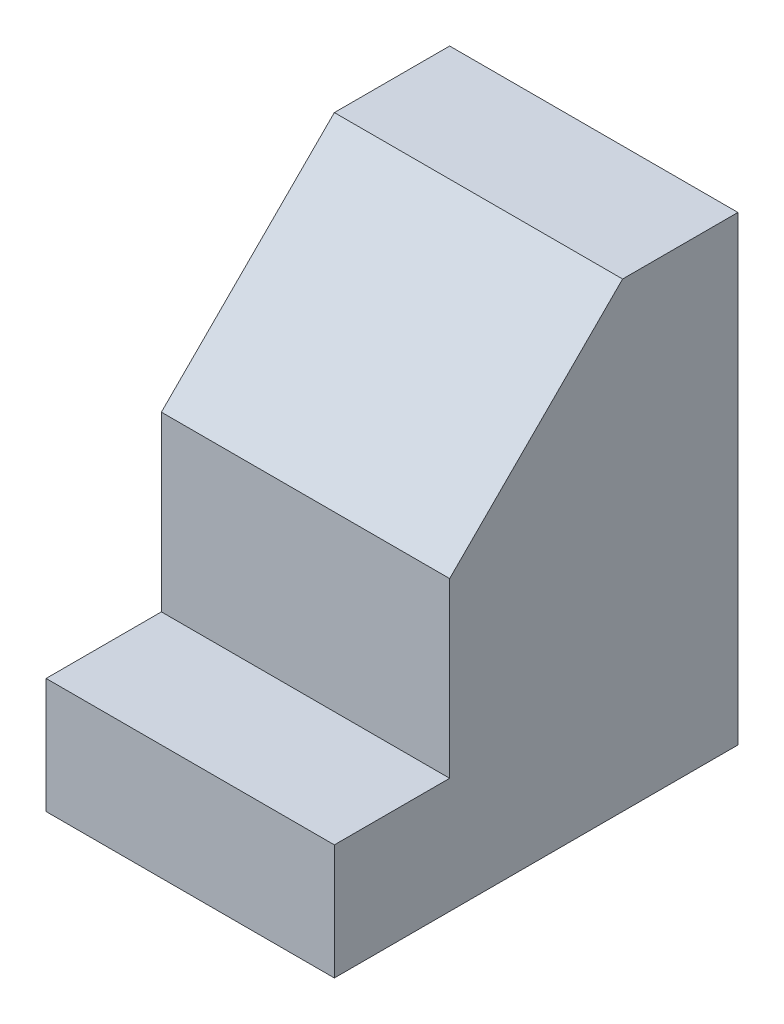
SolidWorks part; units mm, degrees
ref_plane "Ön Düzlem" through (0, 0, 0) normal (0, 0, 1) x (1, 0, 0)
ref_plane "Üst Düzlem" through (0, 0, 0) normal (0, 1, 0) x (1, 0, 0)
ref_plane "Sağ Düzlem" through (0, 0, 0) normal (1, 0, 0) x (0, 0, -1)
sketch "Sketch2" plane through (0, 0, 0) normal (1, 0, 0) x (0, 0, -1)
  line L0 (0, 0) -> (0, 10000)
  line L1 (0, 0) -> (35000, 0)
  line L2 (0, 10000) -> (10000, 10000)
  line L3 (10000, 10000) -> (10000, 40000)
  line L4 (35000, 0) -> (35000, 40000)
  line L5 (35000, 40000) -> (10000, 40000)
extrude "Boss-Extrude1" add sketch "Sketch2" against normal blind 25000 contours L5 L3 L2 L0 L1 L4
chamfer "Chamfer2" distance 15000 angle 45 1 edges at (-12500, 40000, -10000)
